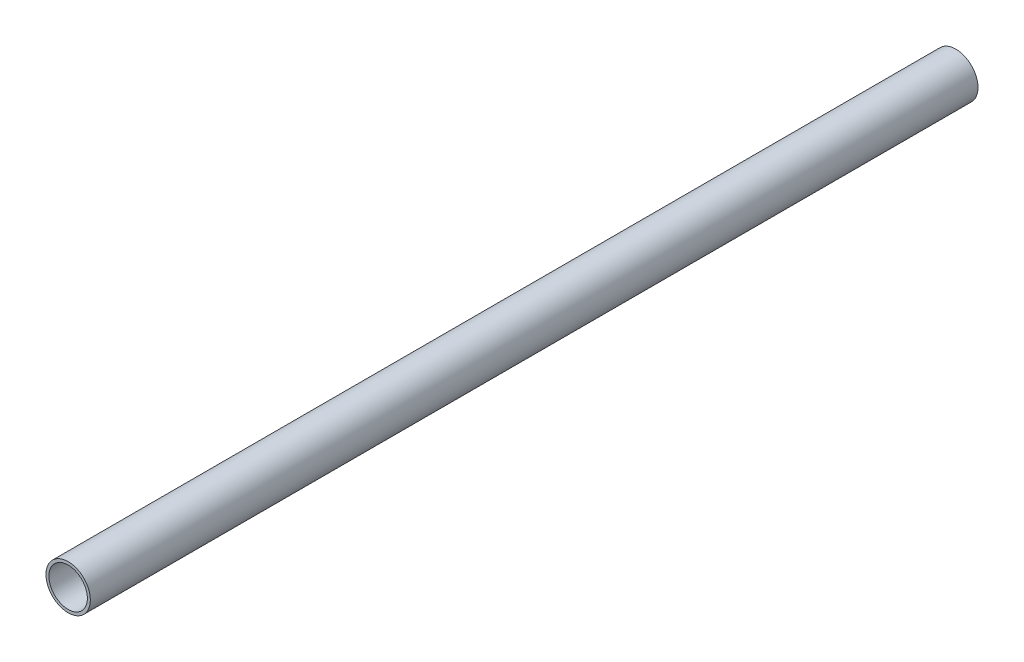
SolidWorks part; units mm, degrees
material "Thornel VCB-20 Carbon Cloth"
ref_plane "Front Plane" through (0, 0, 0) normal (0, 0, 1) x (1, 0, 0)
ref_plane "Top Plane" through (0, 0, 0) normal (0, 1, 0) x (1, 0, 0)
ref_plane "Right Plane" through (0, 0, 0) normal (1, 0, 0) x (0, 0, -1)
sketch "Sketch1" plane through (0, 0, 0) normal (0, 0, 1) x (1, 0, 0)
  circle A0 centre (0, 0) radius 15
  circle A1 centre (0, 0) radius 13
  dimension "D1" = 26
  dimension "D2" = 30
extrude "Boss-Extrude1" add sketch "Sketch1" along normal blind 600
